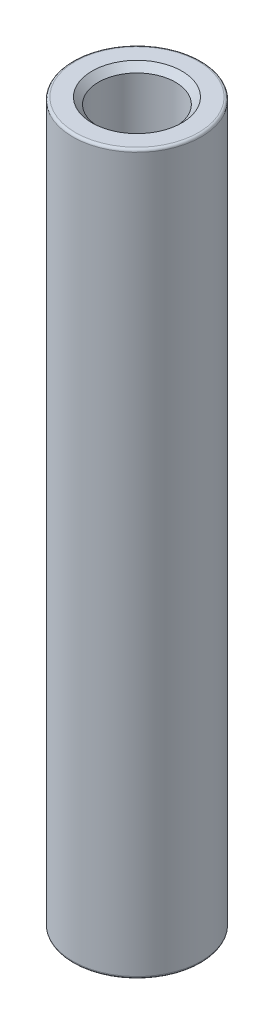
SolidWorks part; units mm, degrees
material "6063-T6"
ref_plane "Front Plane" through (0, 0, 0) normal (0, 0, 1) x (1, 0, 0)
ref_plane "Top Plane" through (0, 0, 0) normal (0, 1, 0) x (1, 0, 0)
ref_plane "Right Plane" through (0, 0, 0) normal (1, 0, 0) x (0, 0, -1)
sketch "Sketch1" plane through (0, 0, 0) normal (0, 1, 0) x (1, 0, 0)
  circle A0 centre (0, 0) radius 2.5
  circle A1 centre (0, 0) radius 1.5
  dimension "D1" = 3
  dimension "D2" = 5
extrude "Boss-Extrude1" add sketch "Sketch1" along normal mid plane 28
chamfer "Chamfer1" distance 0.25 angle 45 2 edges at (0, -14, 1.5) (0, 14, 1.5)
fillet "Fillet1" radius 0.1 2 edges at (0, -14, 2.5) (0, 14, 2.5)
